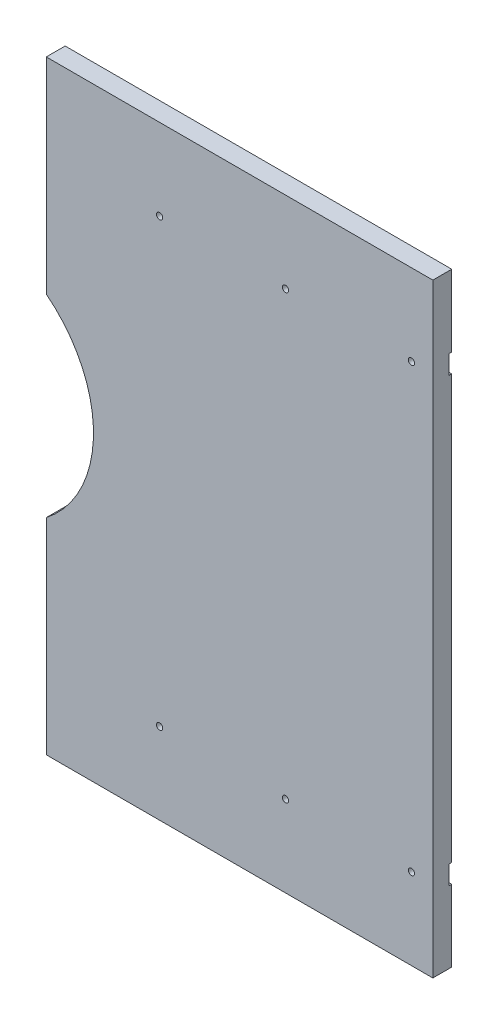
SolidWorks part; units mm, degrees
material "A6061"
ref_plane "前视基准面" through (0, 0, 0) normal (0, 0, 1) x (1, 0, 0)
ref_plane "上视基准面" through (0, 0, 0) normal (0, 1, 0) x (1, 0, 0)
ref_plane "右视基准面" through (0, 0, 0) normal (1, 0, 0) x (0, 0, -1)
sketch "草图1" plane through (0, 0, 0) normal (0, 0, 1) x (1, 0, 0)
  line L1 (153.5, 240) -> (-153.5, 240)
  line L2 (153.5, 240) -> (153.5, -240)
  line L3 (153.5, -240) -> (-153.5, -240)
  line L4 (-153.5, 240) -> (-153.5, -240)
  line L5 (153.5, 240) -> (-153.5, -240) construction
  line L6 (153.5, -240) -> (-153.5, 240) construction
  point P0 (0, 0)
  dimension "D1" = 480
  dimension "D2" = 307
extrude "凸台-拉伸1" add sketch "草图1" along normal blind 15
sketch "草图2" plane through (0, 0, 0) normal (0, 0, -1) x (-1, 0, 0)
  line L0 (-153.5, -240) -> (-153.5, 240) construction
  line L1 (-153.5, 183) -> (153.5, 183)
  line L2 (-153.5, 183) -> (-153.5, 168)
  line L3 (-153.5, 168) -> (153.5, 168)
  line L4 (153.5, 183) -> (153.5, 168)
  line L5 (153.5, 240) -> (153.5, -240) construction
  line L6 (-268.2985, 0) -> (309.4979, 0) construction
  line L7 (153.5, -183) -> (153.5, -168)
  line L8 (-153.5, -168) -> (153.5, -168)
  line L9 (-153.5, -183) -> (-153.5, -168)
  line L10 (-153.5, -183) -> (153.5, -183)
  line L11 (-153.5, 240) -> (153.5, 240) construction
  dimension "D1" = 57
  dimension "D2" = 15
extrude "切除-拉伸1" cut sketch "草图2" against normal blind 2
sketch "草图3" plane through (0, 0, 0) normal (0, 0, -1) x (-1, 0, 0)
  line L0 (0, 93.627) -> (0, -89.0598) construction
  line L1 (-227.0536, 0) -> (219.8767, 0) construction
  line L2 (153.5, 168) -> (153.5, -168) construction
  circle A0 centre (213.5, 0) radius 97.5
  circle A1 centre (-213.5, 0) radius 97.5
  line M3 (153.5, -168) -> (153.5, 168)
  dimension "D2" = 195
  dimension "D1" = 60
extrude "切除-拉伸2" cut sketch "草图3" against normal through all contours A0 M3
sketch "草图4" plane through (0, 0, 2) normal (0, 0, -1) x (-1, 0, 0)
  line L0 (-153.5, -175.5) -> (153.5, -175.5) construction
  line L1 (-153.5, -168) -> (-153.5, -183) construction
  line L2 (153.5, -183) -> (153.5, -168) construction
  line L3 (-179.7749, 0) -> (164.3505, 0) construction
  circle A0 centre (63.5, -175.5) radius 3
  circle A1 centre (-36.5, -175.5) radius 3
  circle A2 centre (-136.5, -175.5) radius 3
  circle A3 centre (-136.5, 175.5) radius 3
  circle A4 centre (-36.5, 175.5) radius 3
  circle A5 centre (63.5, 175.5) radius 3
  dimension "D1" = 90
  dimension "D2" = 6
  dimension "D3" = 3
hole_wizard "M6 螺纹孔1" positions "草图5" profile "草图6" tap size "M6" standard "GB" end condition through all
sketch "草图5" plane through (0, 0, 2) normal (0, 0, -1) x (-1, 0, 0)
  point P0 (63.5, -175.5)
  point P3 (-36.5, -175.5)
  point P6 (-136.5, -175.5)
  point P9 (-136.5, 175.5)
  point P12 (-36.5, 175.5)
  point P15 (63.5, 175.5)
sketch "草图6" plane through (-63.5, -175.5, 2) normal (1, 0, 0) x (0, 1, 0)
  line L0 (0, 0) -> (0, 13)
  line L1 (0, 13) -> (2.5, 13)
  line L2 (2.5, 13) -> (2.5, 0)
  line L5 (2.5, 0) -> (0, 0)
  line L11 (0, -6.35) -> (0, 107.95) construction
  dimension "通孔螺纹孔钻头直径" = 5
  dimension "通孔螺纹孔钻头深度" = 13
cosmetic thread "孔螺蚊线1" parameters "D2"=6
cosmetic thread "孔螺蚊线2" parameters "D2"=6
cosmetic thread "孔螺蚊线3" parameters "D2"=6
cosmetic thread "孔螺蚊线4" parameters "D2"=6
cosmetic thread "孔螺蚊线5" parameters "D2"=6
cosmetic thread "孔螺蚊线6" parameters "D2"=6
